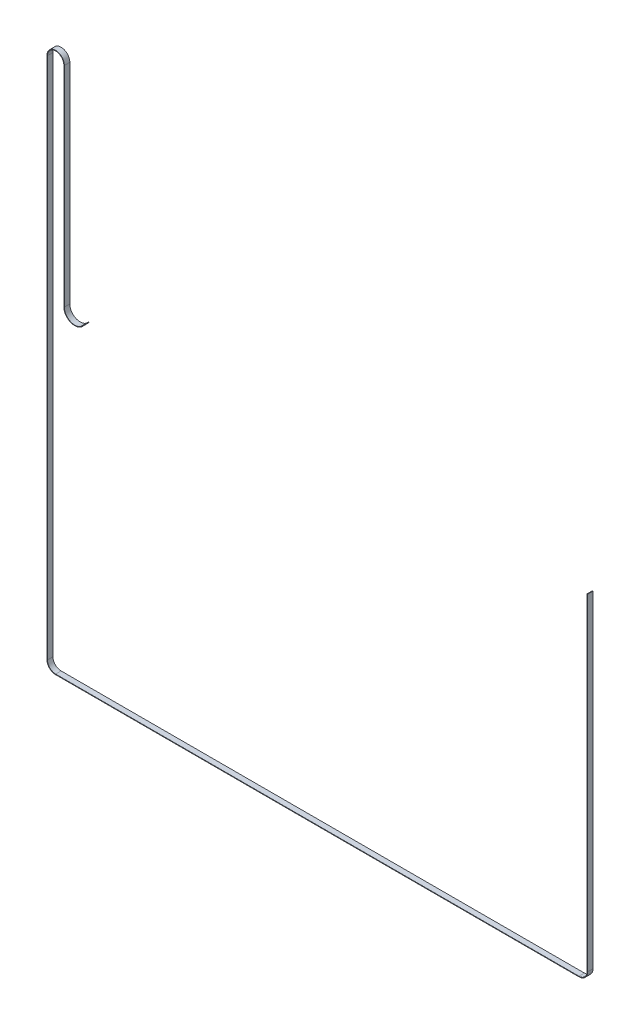
SolidWorks part; units mm, degrees
ref_plane "Ebene vorne" through (0, 0, 0) normal (0, 0, 1) x (1, 0, 0)
ref_plane "Ebene oben" through (0, 0, 0) normal (0, 1, 0) x (1, 0, 0)
ref_plane "Ebene rechts" through (0, 0, 0) normal (1, 0, 0) x (0, 0, -1)
sketch "Skizze1" plane through (0, 0, 0) normal (0, 0, 1) x (1, 0, 0)
  line L0 (-240, 0) -> (240, 0) construction
  line L1 (-240, 0) -> (-240, 480) construction
  line L2 (240, 0) -> (240, 300) construction
  line L3 (-232.5, 480) -> (-232.5, 288)
  line L4 (240, -7.5) -> (-240, -7.5)
  line L5 (-247.5, 0) -> (-247.5, 480)
  line L6 (247.5, 0) -> (247.5, 300)
  circle A0 centre (-240, 480) radius 7.5 construction
  circle A1 centre (-240, 0) radius 7.5 construction
  circle A2 centre (240, 0) radius 7.5 construction
  circle A3 centre (-222.5, 288) radius 10 construction
  arc A4 (-232.5, 480) -> (-247.5, 480) centre (-240, 480) ccw
  arc A5 (-247.5, 0) -> (-240, -7.5) centre (-240, 0) ccw
  arc A6 (247.5, 0) -> (240, -7.5) centre (240, 0) cw
  arc A7 (-232.5, 288) -> (-214.4376, 282.0841) centre (-222.5, 288) ccw
  dimension "D4" = 15
  dimension "D5" = 20
  dimension "D1" = 480
  dimension "D2" = 480
  dimension "D3" = 300
  dimension "D6" = 192
  dimension "D7" = 17.5
extrude "Linear-Austragen-Dünn1" add sketch "Skizze1" along normal mid plane 5 thin thin type one direction reverse wall 0.5
